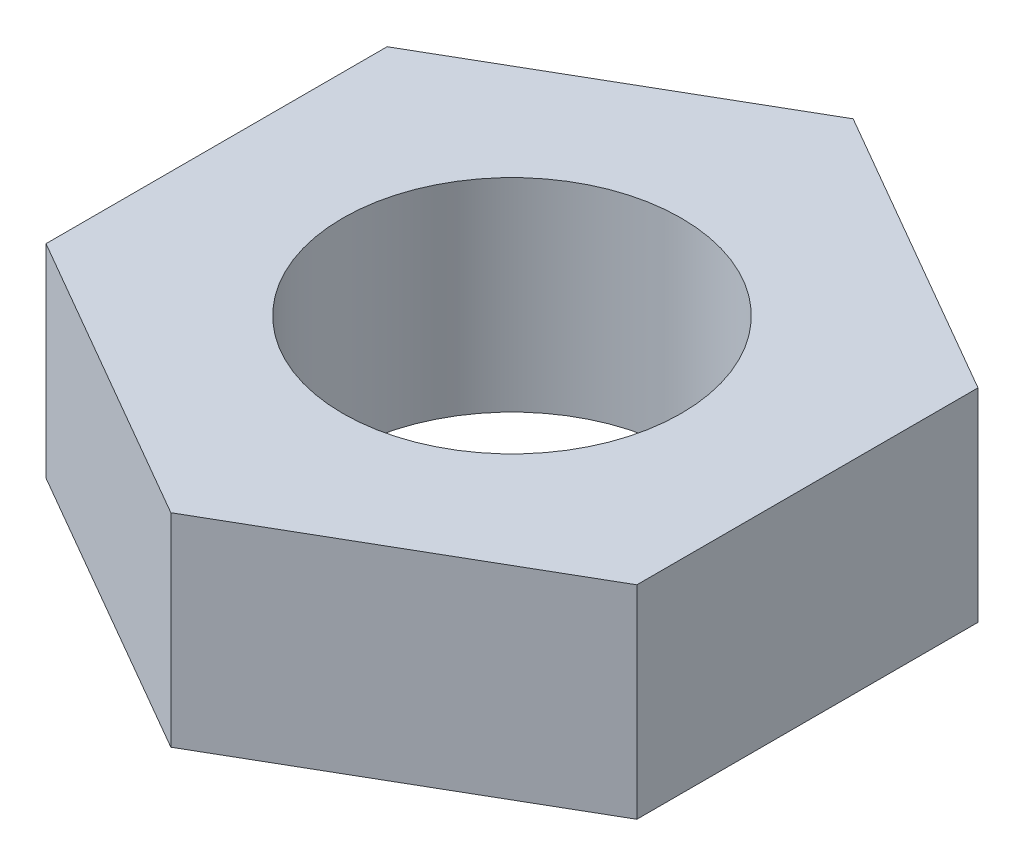
SolidWorks part; units mm, degrees
material "AISI 316 Stainless Steel Sheet (SS)"
ref_plane "Front Plane" through (0, 0, 0) normal (0, 0, 1) x (1, 0, 0)
ref_plane "Top Plane" through (0, 0, 0) normal (0, 1, 0) x (1, 0, 0)
ref_plane "Right Plane" through (0, 0, 0) normal (1, 0, 0) x (0, 0, -1)
sketch "Sketch2" plane through (0, 0, 0) normal (0, 1, 0) x (1, 0, 0)
  line L1 (0, 16) -> (-13.8564, 8)
  line L2 (-13.8564, 8) -> (-13.8564, -8)
  line L3 (-13.8564, -8) -> (0, -16)
  line L4 (0, -16) -> (13.8564, -8)
  line L5 (13.8564, -8) -> (13.8564, 8)
  line L6 (13.8564, 8) -> (0, 16)
  circle A0 centre (0, 0) radius 13.8564 construction
  circle A1 centre (0, 0) radius 7.9375
  dimension "D1" = 15.875
  dimension "D2" = 16
extrude "Boss-Extrude1" add sketch "Sketch2" along normal blind 9.525
equation "\"internalDiameter\"= 5in / 8"
equation "\"D1@Sketch2\"=\"internalDiameter\""
equation "\"nutDepth\"= 3in / 8"
equation "\"D1@Boss-Extrude1\"=\"nutDepth\""
